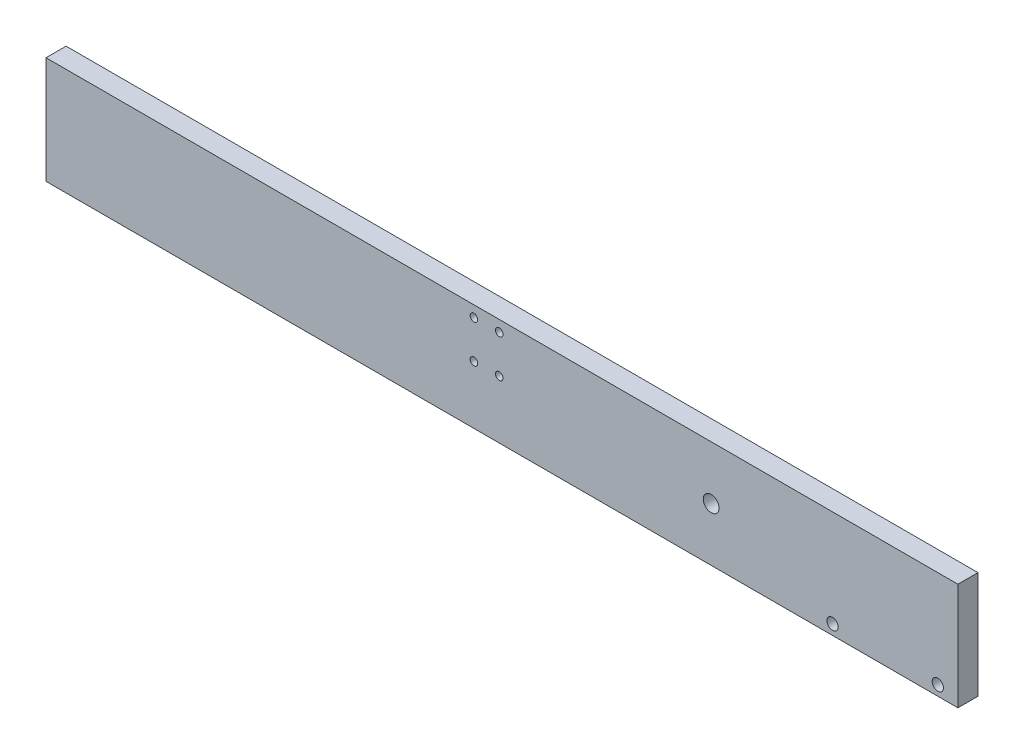
SolidWorks part; units mm, degrees
ref_plane "Front Plane" through (0, 0, 0) normal (0, 0, 1) x (1, 0, 0)
ref_plane "Top Plane" through (0, 0, 0) normal (0, 1, 0) x (1, 0, 0)
ref_plane "Right Plane" through (0, 0, 0) normal (1, 0, 0) x (0, 0, -1)
sketch "Sketch1" plane through (0, 0, 0) normal (0, 0, 1) x (1, 0, 0)
  point P0 (0, 0)
  line B0 (0, 33.85) -> (0, 0)
  line B1 (0, 0) -> (288.29, 0)
  line B2 (288.29, 0) -> (288.29, 33.85)
  line B3 (288.29, 33.85) -> (0, 33.85)
  circle B4 centre (281.94, 3.175) radius 1.7859
  circle B5 centre (210.29, 16.925) radius 2.5
  circle B6 centre (135.29, 30.35) radius 1.2
  circle B7 centre (135.29, 18.35) radius 1.2
  circle B8 centre (143.29, 18.35) radius 1.2
  circle B9 centre (143.29, 30.35) radius 1.2
  circle B10 centre (248.64, 3.175) radius 1.7859
sketch_block_instance "Right_Side_IC-1"
sketch_block "Right_Side_IC" parameters "D3"=3.5719, "D1"=6.35, "D2"=33.3, "D4"=3.175
extrude "Boss-Extrude1" add sketch "Sketch1" along normal blind 6.35
